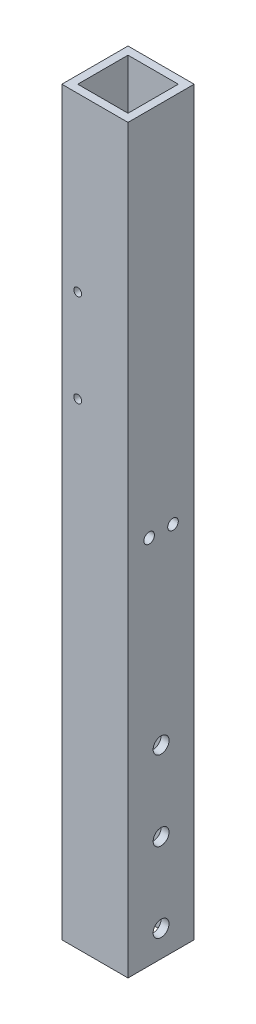
SolidWorks part; units mm, degrees
material "氧化铝"
ref_plane "前视基准面" through (0, 0, 0) normal (0, 0, 1) x (1, 0, 0)
ref_plane "上视基准面" through (0, 0, 0) normal (0, 1, 0) x (1, 0, 0)
ref_plane "右视基准面" through (0, 0, 0) normal (1, 0, 0) x (0, 0, -1)
other "Configuration Table"
sketch "草图1" plane through (0, 0, 0) normal (0, 1, 0) x (1, 0, 0)
  line L1 (0, 0) -> (25, 0)
  line L2 (0, 0) -> (0, 25)
  line L3 (0, 25) -> (25, 25)
  line L4 (25, 0) -> (25, 25)
  line L5 (3, 3) -> (22, 3)
  line L6 (3, 3) -> (3, 22)
  line L7 (3, 22) -> (22, 22)
  line L8 (22, 3) -> (22, 22)
  dimension "D1" = 25
  dimension "D2" = 25
  dimension "D3" = 3
  dimension "D4" = 3
  dimension "D5" = 3
  dimension "D6" = 3
extrude "凸台-拉伸1" add sketch "草图1" along normal blind 280
sketch "草图2" plane through (0, 0, 0) normal (1, 0, 0) x (0, 0, -1)
  line L0 (12.5, -31.3312) -> (12.5, 287.2487) construction
  line L1 (12.5, 10) -> (12.5, 40) construction
  line L3 (0, 0) -> (25, 0) construction
  circle A0 centre (12.5, 10) radius 3
  circle A2 centre (12.5, 40) radius 3
  circle A3 centre (12.5, 70) radius 3
  circle A4 centre (17, 140) radius 2
  circle A5 centre (8, 140) radius 2
  dimension "D2" = 6
  dimension "D3" = 3
  dimension "D6" = 4
  dimension "D1" = 12.5
  dimension "D4" = 10
  dimension "D5" = 30
  dimension "D7" = 9
  dimension "D8" = 140
extrude "切除-拉伸1" cut sketch "草图2" along normal through all
sketch "草图3" plane through (0, 0, 0) normal (0, 0, 1) x (1, 0, 0)
  line L0 (6, -7.4812) -> (6, 258.86) construction
  line L1 (6, 180) -> (6, 215) construction
  circle A0 centre (6, 180) radius 1.5
  circle A1 centre (6, 215) radius 1.5
  dimension "D2" = 3
  dimension "D1" = 6
  dimension "D4" = 180
  dimension "D5" = 35
  dimension "D3" = 2
extrude "切除-拉伸2" cut sketch "草图3" against normal through all both
